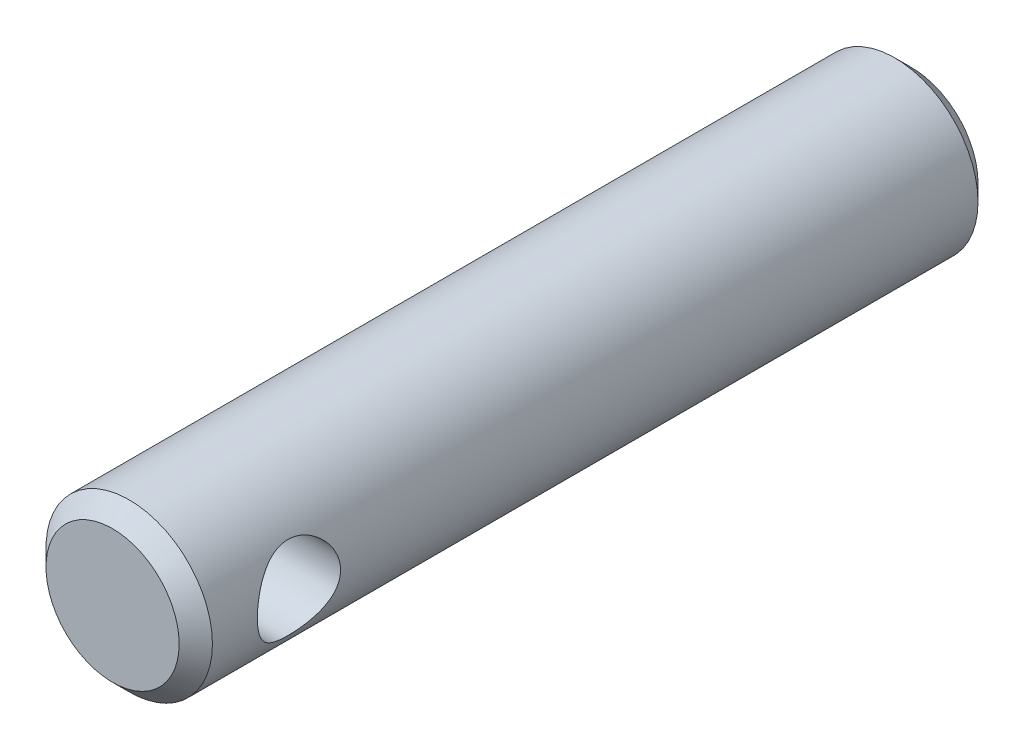
SolidWorks part; units mm, degrees
ref_plane "正面" through (0, 0, 0) normal (0, 0, 1) x (1, 0, 0)
ref_plane "平面" through (0, 0, 0) normal (0, 1, 0) x (1, 0, 0)
ref_plane "右側面" through (0, 0, 0) normal (1, 0, 0) x (0, 0, -1)
sketch "ｽｹｯﾁ1" plane through (0, 0, 0) normal (0, 0, 1) x (1, 0, 0)
  circle A0 centre (0, 0) radius 5
  dimension "D1" = 10
extrude "ﾎﾞｽ - 押し出し1" add sketch "ｽｹｯﾁ1" along normal mid plane 48
chamfer "面取り1" distance 1 angle 45 2 edges at (5, 0, -24) (5, 0, 24)
sketch "ｽｹｯﾁ4" plane through (0, 0, 0) normal (1, 0, 0) x (0, 0, -1)
  circle A0 centre (-17.8, 0) radius 3.5 construction
  circle A1 centre (-17.8, 0) radius 3.5 construction
hole_wizard "M6x1.0 ねじ穴用ねじ下穴ﾄﾞﾘﾙ1" positions "ｽｹｯﾁ5" profile "ｽｹｯﾁ6" hole size "M6x1.0" standard "JIS"
sketch "ｽｹｯﾁ5" plane through (0, 0, 0) normal (1, 0, 0) x (0, 0, -1)
  point P0 (-17.8, 0)
sketch "ｽｹｯﾁ6" plane through (0, 0, 17.8) normal (0, 1, 0) x (0, 0, 1)
  line L0 (0, 0) -> (0, 5)
  line L1 (0, 5) -> (2.5, 5)
  line L2 (2.5, 5) -> (2.5, 0)
  line L5 (2.5, 0) -> (0, 0)
  line L11 (0, -6.35) -> (0, 107.95) construction
  dimension "通し穴の直径" = 5
  dimension "通し穴の深さ" = 5
mirror "ﾐﾗｰ1" about plane through (0, 0, 0) normal (1, 0, 0) of "M6x1.0 ねじ穴用ねじ下穴ﾄﾞﾘﾙ1"
